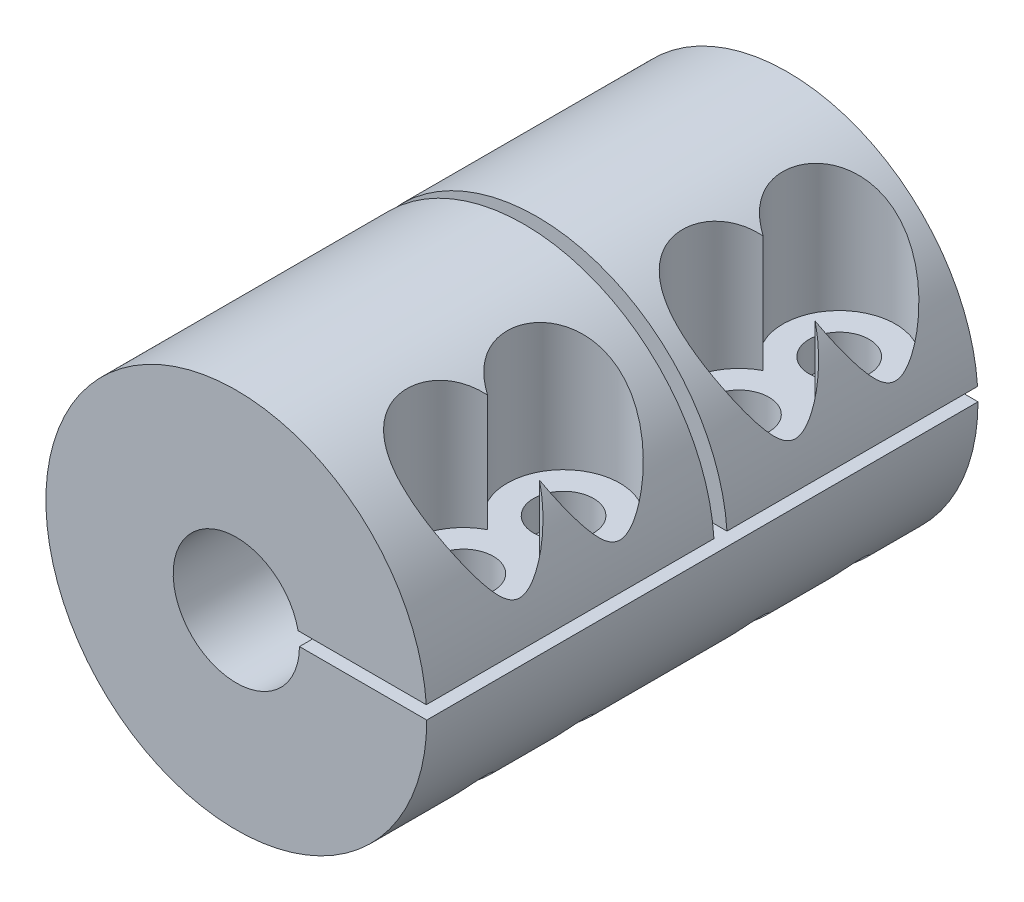
SolidWorks part; units mm, degrees
ref_plane "Front Plane" through (0, 0, 0) normal (0, 0, 1) x (1, 0, 0)
ref_plane "Top Plane" through (0, 0, 0) normal (0, 1, 0) x (1, 0, 0)
ref_plane "Right Plane" through (0, 0, 0) normal (1, 0, 0) x (0, 0, -1)
sketch "Sketch1" plane through (0, 0, 0) normal (0, 1, 0) x (1, 0, 0)
  line L0 (0, 0) -> (0, 69.6288) construction
  line L1 (3.175, 44.927) -> (3.175, 29.052)
  line L2 (3.175, 29.052) -> (4, 29.052)
  line L3 (4, 29.052) -> (4, 10.002)
  line L4 (4, 10.002) -> (12.065, 10.002)
  line L5 (12.065, 10.002) -> (12.065, 44.927)
  line L6 (12.065, 44.927) -> (3.175, 44.927)
  dimension "D1" = 6.35
  dimension "D2" = 8
  dimension "D3" = 24.13
  dimension "D4" = 15.875
  dimension "D5" = 19.05
revolve "Revolve1" add sketch "Sketch1" angle 360 about L0
ref_plane "Plane1" through (0, 0, -29.052) normal (0, 0, 1) x (1, 0, 0)
sketch "Sketch4" plane through (0, 0, 0) normal (0, 1, 0) x (1, 0, 0)
  line L0 (-12.065, 44.927) -> (-12.065, 10.002) construction
  line L1 (-12.065, 28.2265) -> (12.065, 28.2265)
  line L2 (-12.065, 28.2265) -> (-12.065, 29.052)
  line L3 (-12.065, 29.052) -> (12.065, 29.052)
  line L4 (12.065, 28.2265) -> (12.065, 29.052)
  line L5 (-8.8357, 29.052) -> (8.8357, 29.052) construction
  line L6 (12.065, 10.002) -> (12.065, 44.927) construction
  dimension "D1" = 0.8255
extrude "Cut-Extrude1" cut sketch "Sketch4" along normal through all
sketch "Sketch5" plane through (0, 0, 0) normal (1, 0, 0) x (0, 0, -1)
  line L0 (10.002, 4) -> (10.002, -4) construction
  line L1 (10.002, 0) -> (44.927, 0)
  line L2 (10.002, 0) -> (10.002, 0.8255)
  line L3 (10.002, 0.8255) -> (44.927, 0.8255)
  line L4 (44.927, 0) -> (44.927, 0.8255)
  line L5 (44.927, -12.065) -> (44.927, 12.065) construction
  dimension "D1" = 0.8255
extrude "Cut-Extrude2" cut sketch "Sketch5" along normal through all
hole_wizard "#6-32 Tapped Hole1" positions "Sketch7" profile "Sketch6" tap size "#6-32" standard "Ansi Inch"
sketch "Sketch7" plane through (0, 0, 0) normal (0, 1, 0) x (-1, 0, 0)
  line L0 (-12.065, -10.002) -> (-4, -10.002) construction
  line L1 (-12.065, -44.927) -> (-3.175, -44.927) construction
  point P0 (-8.0325, -16.352)
  point P4 (-8.0325, -22.702)
  point P6 (-8.0325, -33.8145)
  point P8 (-8.0325, -40.1645)
  point P11 (-8.0325, -10.002)
  dimension "D1" = 6.35
  dimension "D2" = 6.35
  dimension "D3" = 6.35
  dimension "D4" = 4.7625
sketch "Sketch6" plane through (8.0325, 0, -16.352) normal (1, 0, 0) x (0, 0, 1)
  line L0 (0, 0) -> (0, 11.9887)
  line L1 (0, 11.9887) -> (1.3525, 11.176)
  line L2 (1.3525, 11.176) -> (1.3525, 0)
  line L5 (1.3525, 0) -> (0, 0)
  line L10 (0, 11.9887) -> (-1.3526, 11.176) construction
  line L11 (0, -6.35) -> (0, 107.95) construction
  dimension "Tap Drill Dia." = 2.7051
  dimension "Tap Drill Depth" = 11.176
  dimension "Drill Angle" = 118
cosmetic thread "Hole Thread1" parameters "D1"=7.112, "D2"=3.5052
cosmetic thread "Hole Thread2" parameters "D1"=7.112, "D2"=3.5052
cosmetic thread "Hole Thread3" parameters "D1"=7.112, "D2"=3.5052
cosmetic thread "Hole Thread4" parameters "D1"=7.112, "D2"=3.5052
ref_plane "Plane2" through (0, 12.7, 0) normal (0, 1, 0) x (-1, 0, 0)
hole_wizard "CBORE for #6 Socket Head Cap Screw1" positions "Sketch10" profile "Sketch9" counterbore size "#6" standard "Ansi Inch"
sketch "Sketch10" plane through (0, 12.7, 0) normal (0, 1, 0) x (-1, 0, 0)
  circle A0 centre (-8.0325, -16.352) radius 1.3525 construction
  circle A1 centre (-8.0325, -22.702) radius 1.3525 construction
  circle A2 centre (-8.0325, -33.8145) radius 1.3526 construction
  circle A3 centre (-8.0325, -40.1645) radius 1.3525 construction
  point P1 (-8.0325, -16.352)
  point P3 (-8.0325, -22.702)
  point P5 (-8.0325, -33.8145)
  point P7 (-8.0325, -40.1645)
sketch "Sketch9" plane through (8.0325, 12.7, -16.352) normal (1, 0, 0) x (0, 0, 1)
  line L0 (0, 0) -> (0, 11.8745)
  line L1 (0, 11.8745) -> (1.8986, 11.8745)
  line L3 (1.8986, 11.8745) -> (1.8986, 9.8552)
  line L4 (1.8986, 9.8552) -> (3.5725, 9.8552)
  line L5 (3.5725, 9.8552) -> (3.5725, 0)
  line L7 (3.5725, 0) -> (0, 0)
  line L11 (0, -6.35) -> (0, 107.95) construction
  dimension "Thru Hole Dia." = 3.7973
  dimension "Thru Hole Depth" = 11.8745
  dimension "C'Bore Dia." = 7.145
  dimension "C'Bore Depth" = 9.8552
